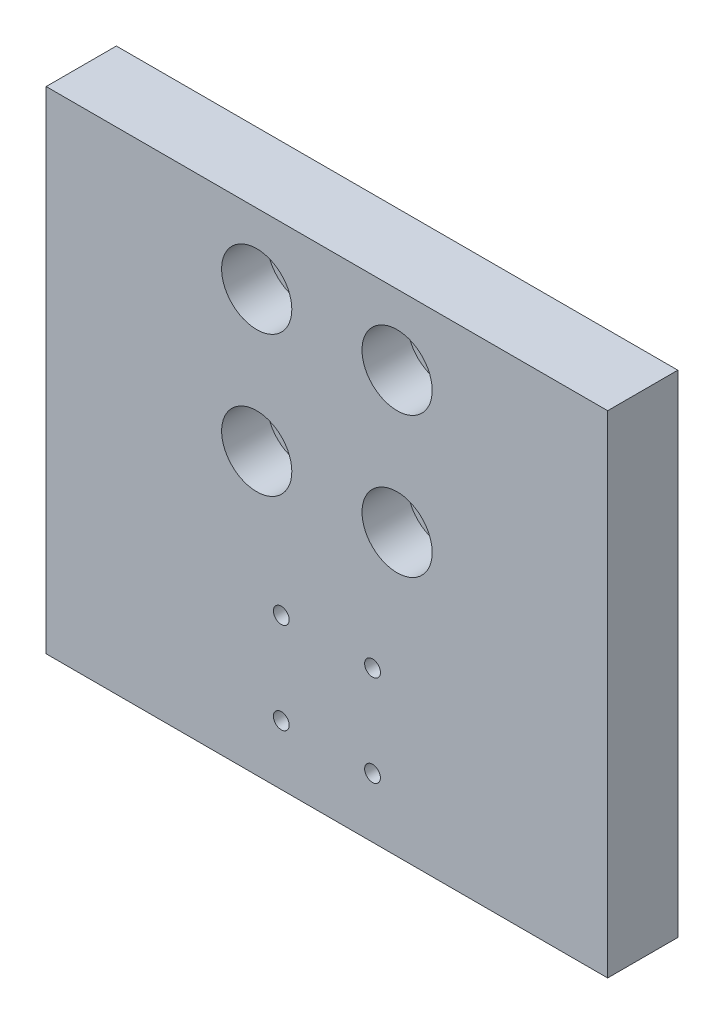
SolidWorks part; units mm, degrees
material "6061 合金"
ref_plane "前视基准面" through (0, 0, 0) normal (0, 0, 1) x (1, 0, 0)
ref_plane "上视基准面" through (0, 0, 0) normal (0, 1, 0) x (1, 0, 0)
ref_plane "右视基准面" through (0, 0, 0) normal (1, 0, 0) x (0, 0, -1)
other "Configuration Table"
sketch "Sketch1" plane through (0, 0, 0) normal (0, 0, 1) x (1, 0, 0)
  line L1 (-80, -170) -> (80, -170)
  line L2 (-80, -170) -> (-80, -30)
  line L3 (-80, -30) -> (80, -30)
  line L4 (80, -170) -> (80, -30)
extrude "Boss-Extrude1" add sketch "Sketch1" along normal blind 20
sketch "Sketch2" plane through (0, 0, 0) normal (0, 0, 1) x (1, 0, 0)
  circle A0 centre (-20, -50) radius 6.75
  circle A1 centre (-20, -90) radius 6.75
  circle A2 centre (20, -50) radius 6.75
  circle A3 centre (20, -90) radius 6.75
extrude "Cut-Extrude1" cut sketch "Sketch2" against normal through all and the other way through all
ref_plane "Plane1" through (0, 0, 20) normal (0, 0, 1) x (1, 0, 0)
sketch "Sketch3" plane through (0, 0, 20) normal (0, 0, 1) x (1, 0, 0)
  circle A0 centre (-20, -50) radius 10
  circle A1 centre (-20, -90) radius 10
  circle A2 centre (20, -50) radius 10
  circle A3 centre (20, -90) radius 10
extrude "Cut-Extrude3" cut sketch "Sketch3" against normal blind 13
sketch "Sketch4" plane through (0, 0, 0) normal (0, 0, 1) x (1, 0, 0)
  circle A0 centre (-13, -127) radius 2.25
  circle A1 centre (-13, -153) radius 2.25
  circle A2 centre (13, -127) radius 2.25
  circle A3 centre (13, -153) radius 2.25
extrude "Cut-Extrude4" cut sketch "Sketch4" against normal through all and the other way through all
sketch "Sketch5" plane through (0, 0, 0) normal (0, 0, 1) x (1, 0, 0)
  circle A0 centre (-13, -127) radius 4
  circle A1 centre (-13, -153) radius 4
  circle A2 centre (13, -127) radius 4
  circle A3 centre (13, -153) radius 4
extrude "Cut-Extrude6" cut sketch "Sketch5" along normal blind 4.5
